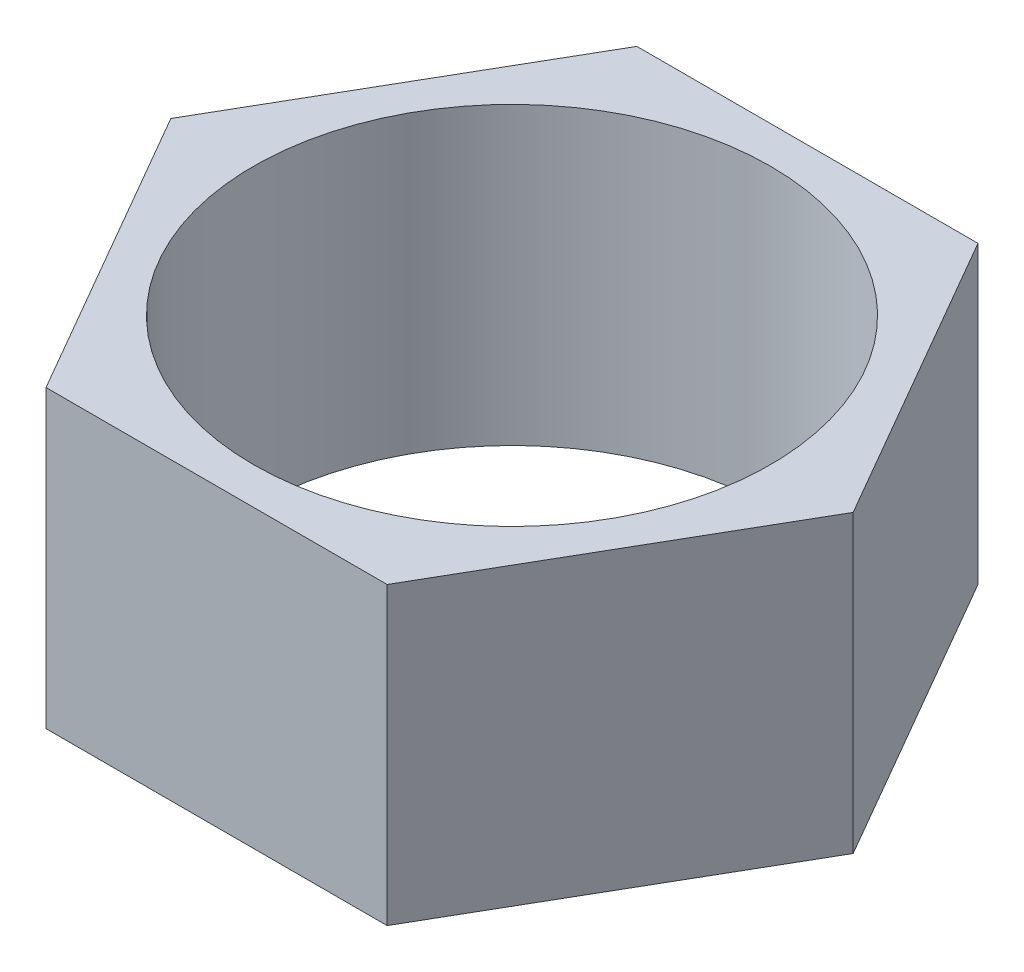
SolidWorks part; units mm, degrees
ref_plane "Front Plane" through (0, 0, 0) normal (0, 0, 1) x (1, 0, 0)
ref_plane "Top Plane" through (0, 0, 0) normal (0, 1, 0) x (1, 0, 0)
ref_plane "Right Plane" through (0, 0, 0) normal (1, 0, 0) x (0, 0, -1)
sketch "Sketch1" plane through (0, 0, 0) normal (0, 1, 0) x (1, 0, 0)
  line L1 (11.547, 0) -> (5.7735, 10)
  line L2 (5.7735, 10) -> (-5.7735, 10)
  line L3 (-5.7735, 10) -> (-11.547, 0)
  line L4 (-11.547, 0) -> (-5.7735, -10)
  line L5 (-5.7735, -10) -> (5.7735, -10)
  line L6 (5.7735, -10) -> (11.547, 0)
  circle A0 centre (0, 0) radius 8.75
  circle A1 centre (0, 0) radius 10 construction
  dimension "D1" = 17.5
  dimension "D2" = 0
  dimension "D3" = 0
  dimension "D4" = 11.547
  dimension "D5" = 10
extrude "Boss-Extrude1" add sketch "Sketch1" along normal blind 10
